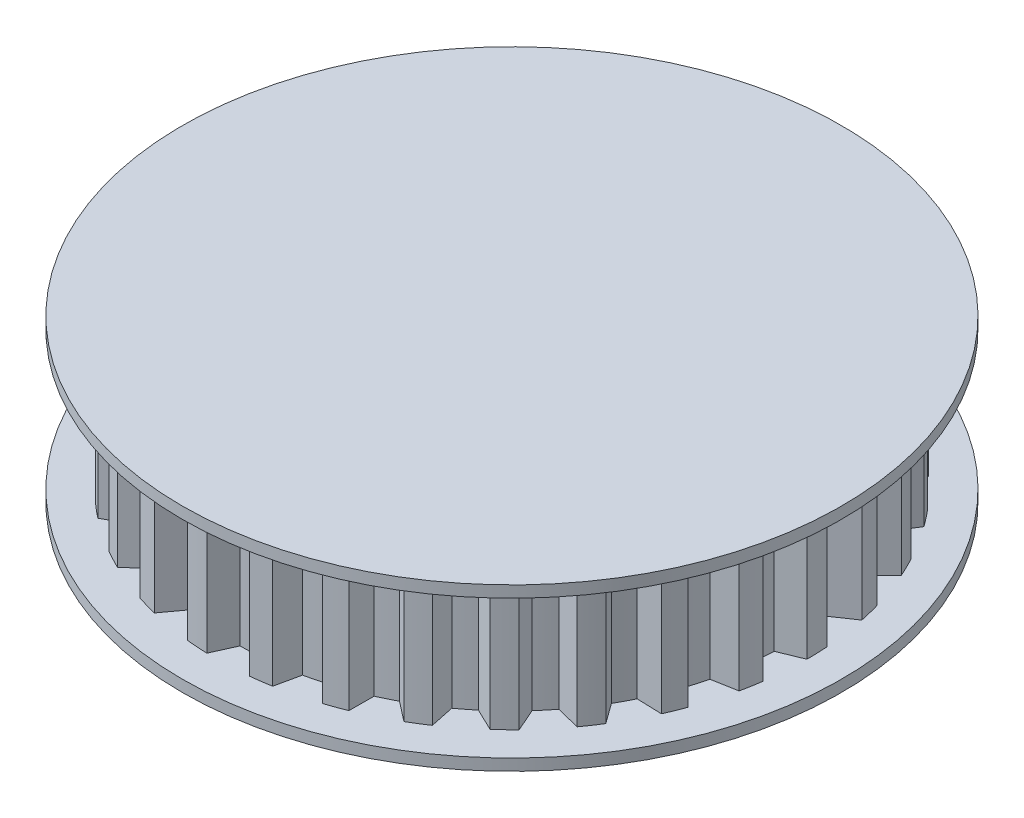
SolidWorks part; units mm, degrees
ref_plane "Front Plane" through (0, 0, 0) normal (0, 0, 1) x (1, 0, 0)
ref_plane "Top Plane" through (0, 0, 0) normal (0, 1, 0) x (1, 0, 0)
ref_plane "Right Plane" through (0, 0, 0) normal (1, 0, 0) x (0, 0, -1)
sketch "Sketch1" plane through (0, 0, 0) normal (0, 1, 0) x (1, 0, 0)
  circle A0 centre (0, 0) radius 28.575
  dimension "D1" = 57.15
extrude "Boss-Extrude1" add sketch "Sketch1" along normal blind 1
sketch "Sketch2" plane through (0, 1, 0) normal (0, 1, 0) x (1, 0, 0)
  line L0 (0, 0) -> (25.575, 0)
  line L4 (0, 0) -> (25.0161, 5.3173)
  line L5 (25.5127, 1.784) -> (23.4459, 2.4643)
  line L6 (25.0161, 5.3173) -> (23.2168, 4.0938)
  arc A0 (25.575, 0) -> (25.5127, 1.784) centre (0, 0) ccw
  circle A3 centre (0, 0) radius 28.575 construction
  arc A4 (23.4459, 2.4643) -> (23.2168, 4.0938) centre (0, 0) ccw
  dimension "D1" = 3
  dimension "D2" = 12
extrude "Boss-Extrude3" add sketch "Sketch2" along normal blind 12
pattern_circular "CirPattern2" count 30 over 360 about axis through (0, 0, 0) along (0, 1, 0) of "Boss-Extrude3"
sketch "Sketch3" plane through (0, 13, 0) normal (0, 1, 0) x (1, 0, 0)
  circle A0 centre (0, 0) radius 28.575
  circle A1 centre (0, 0) radius 28.575 construction
  dimension "D1" = 0
extrude "Boss-Extrude4" add sketch "Sketch3" along normal blind 1
sketch "Sketch4" plane through (0, 14, 0) normal (0, 1, 0) x (1, 0, 0)
  circle A0 centre (0, 0) radius 8.7586
